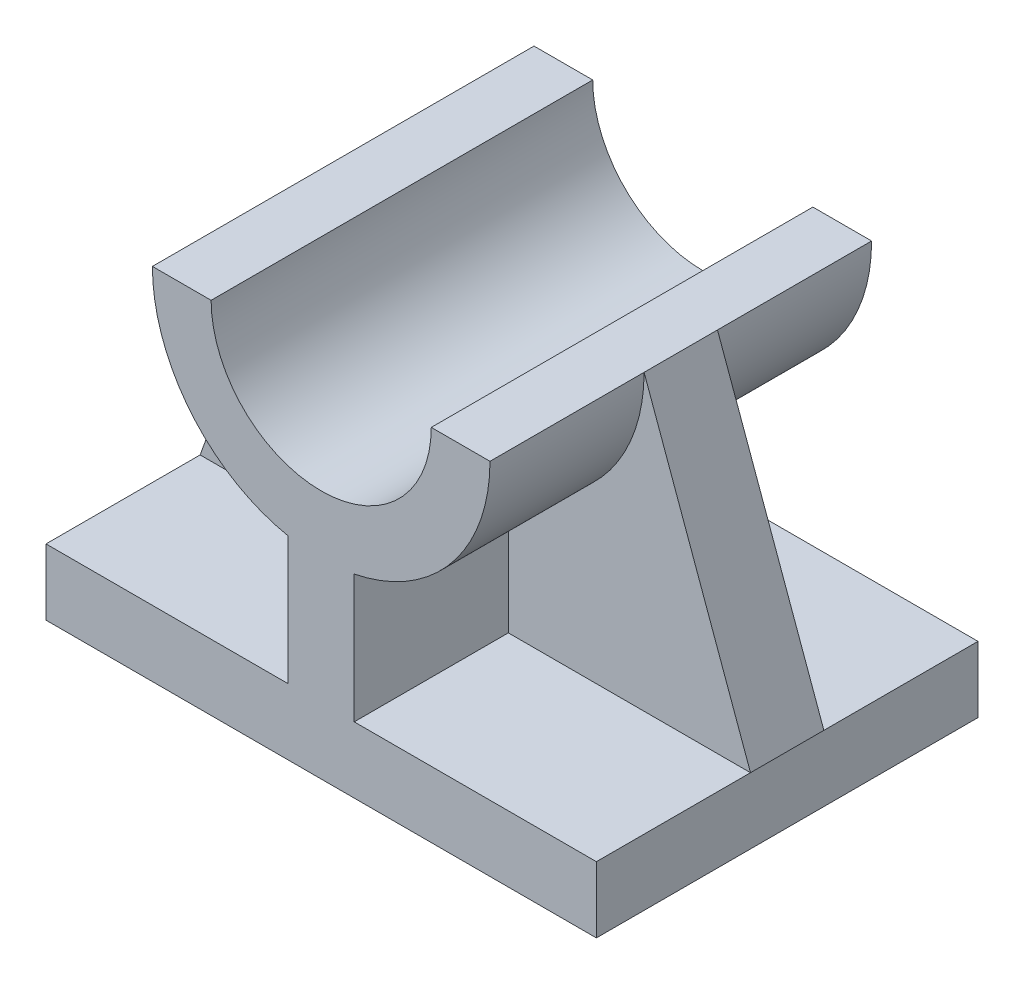
SolidWorks part; units mm, degrees
ref_plane "Front Plane" through (0, 0, 0) normal (0, 0, 1) x (1, 0, 0)
ref_plane "Top Plane" through (0, 0, 0) normal (0, 1, 0) x (1, 0, 0)
ref_plane "Right Plane" through (0, 0, 0) normal (1, 0, 0) x (0, 0, -1)
sketch "Sketch1" plane through (0, 0, 0) normal (0, 0, 1) x (1, 0, 0)
  line L0 (-23, 44.5) -> (-15, 44.5)
  line L1 (-37.5, 4.5) -> (-4.5, 4.5)
  line L2 (-37.5, 4.5) -> (-37.5, -4.5)
  line L3 (-37.5, -4.5) -> (37.5, -4.5)
  line L4 (37.5, 4.5) -> (37.5, -4.5)
  line L5 (-37.5, 4.5) -> (37.5, -4.5) construction
  line L6 (-37.5, -4.5) -> (37.5, 4.5) construction
  line L8 (-4.5, 21.9445) -> (-4.5, 4.5)
  line L10 (4.5, 21.9445) -> (4.5, 4.5)
  line L11 (15, 44.5) -> (23, 44.5)
  line L12 (4.5, 4.5) -> (37.5, 4.5)
  arc A0 (-15, 44.5) -> (15, 44.5) centre (0, 44.5) ccw
  arc A2 (-23, 44.5) -> (-4.5, 21.9445) centre (0, 44.5) ccw
  arc A3 (4.5, 21.9445) -> (23, 44.5) centre (0, 44.5) ccw
  circle A4 centre (0, 44.5) radius 23 construction
  circle A5 centre (0, 44.5) radius 15 construction
  point P0 (0, 0)
  point P9 (14.3446, 48.8856)
  point P15 (23, 44.5)
  dimension "D2" = 9
  dimension "D3" = 8
extrude "Boss-Extrude2" add sketch "Sketch1" along normal mid plane 52
sketch "Sketch2" plane through (0, 0, 0) normal (0, 0, 1) x (1, 0, 0)
  line L0 (23, 44.5) -> (37.5, 4.5)
rib "Rib1" sketch "Sketch2" sketch "Sketch2" thickness 10 extrusion direction parallel to sketch draft on no parameters "D1"=10
mirror "Mirror1" about plane through (0, 0, 0) normal (1, 0, 0) of "Rib1"
